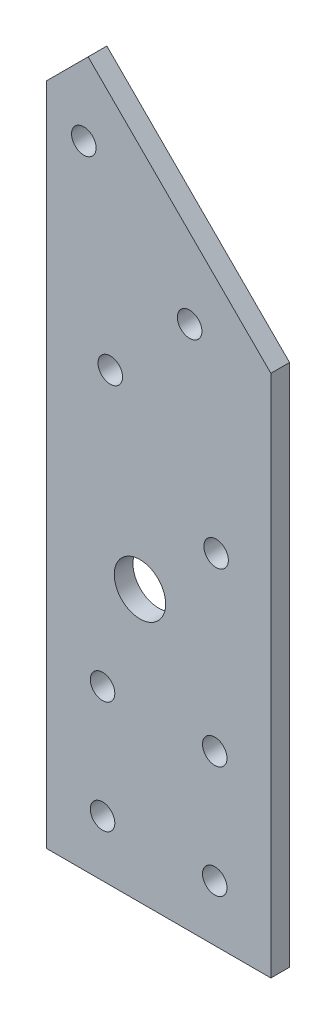
SolidWorks part; units mm, degrees
material "6061-T6 (SS)"
ref_plane "Front" through (0, 0, 0) normal (0, 0, 1) x (1, 0, 0)
ref_plane "Top" through (0, 0, 0) normal (0, 1, 0) x (1, 0, 0)
ref_plane "Right" through (0, 0, 0) normal (1, 0, 0) x (0, 0, -1)
sketch "Sketch1" plane through (0, 0, 0) normal (0, 0, 1) x (1, 0, 0)
  line L0 (0, 0) -> (76.2, 0)
  line L1 (76.2, 0) -> (76.2, 177.8)
  line L2 (76.2, 177.8) -> (14.1602, 239.8398)
  line L3 (0, 225.6796) -> (0, 0)
  line L4 (14.1602, 239.8398) -> (0, 225.6796)
  dimension "D1" = 76.2
  dimension "D2" = 177.8
  dimension "D3" = 45
  dimension "D4" = 20.0255
extrude "Boss-Extrude1" add sketch "Sketch1" along normal blind 6.35
hole_wizard "21/64 (0.32813) Diameter Hole1" positions "Sketch2" profile "Sketch3" hole size "21/64" standard "ANSI Inch" end condition through all
sketch "Sketch2" plane through (0, 0, 6.35) normal (0, 0, 1) x (1, 0, 0)
  line L0 (76.2, 0) -> (76.2, 177.8) construction
  line L1 (0, 0) -> (76.2, 0) construction
  point P0 (57.15, 19.05)
  dimension "D1" = 19.05
  dimension "D2" = 19.05
sketch "Sketch3" plane through (57.15, 19.05, 6.35) normal (1, 0, 0) x (0, -1, 0)
  line L0 (0, 0) -> (0, 6.35)
  line L1 (0, 6.35) -> (4.1673, 6.35)
  line L2 (4.1673, 6.35) -> (4.1673, 0)
  line L5 (4.1673, 0) -> (0, 0)
  line L11 (0, -6.35) -> (0, 107.95) construction
  dimension "Thru Hole Dia." = 8.3345
  dimension "Thru Hole Depth" = 6.35
pattern_linear "LPattern1" count 2 spacing 38.1 along (-1, 0, 0) count 2 spacing 38.1 along (0, 1, 0) of "21/64 (0.32813) Diameter Hole1"
hole_wizard "21/64 (0.32813) Diameter Hole2" positions "Sketch4" profile "Sketch5" hole size "21/64" standard "ANSI Inch" end condition through all
sketch "Sketch4" plane through (0, 0, 6.35) normal (0, 0, 1) x (1, 0, 0)
  line L0 (76.2, 177.8) -> (14.1602, 239.8398) construction
  line L1 (0, 225.6796) -> (0, 0) construction
  point P0 (12.7, 214.3592)
  dimension "D1" = 19.05
  dimension "D2" = 12.7
sketch "Sketch5" plane through (12.7, 214.3592, 6.35) normal (1, 0, 0) x (0, -1, 0)
  line L0 (0, 0) -> (0, 6.35)
  line L1 (0, 6.35) -> (4.1673, 6.35)
  line L2 (4.1673, 6.35) -> (4.1673, 0)
  line L5 (4.1673, 0) -> (0, 0)
  line L11 (0, -6.35) -> (0, 107.95) construction
  dimension "Thru Hole Dia." = 8.3345
  dimension "Thru Hole Depth" = 6.35
pattern_linear "LPattern2" count 3 spacing 50.8 along (0.7071, -0.7071, 0) count 2 spacing 38.1 along (-0.7071, -0.7071, 0) skipping (0, 1), (2, 0) of "21/64 (0.32813) Diameter Hole2"
hole_wizard "11/16 (0.6875) Diameter Hole1" positions "Sketch6" profile "Sketch7" hole size "11/16" standard "ANSI Inch" end condition through all
sketch "Sketch6" plane through (0, 0, 6.35) normal (0, 0, 1) x (1, 0, 0)
  line L0 (0, 225.6796) -> (0, 0) construction
  line L1 (0, 0) -> (76.2, 0) construction
  point P0 (31.75, 92.075)
  dimension "D1" = 31.75
  dimension "D2" = 92.075
sketch "Sketch7" plane through (31.75, 92.075, 6.35) normal (1, 0, 0) x (0, -1, 0)
  line L0 (0, 0) -> (0, 6.35)
  line L1 (0, 6.35) -> (8.7312, 6.35)
  line L2 (8.7312, 6.35) -> (8.7312, 0)
  line L5 (8.7312, 0) -> (0, 0)
  line L11 (0, -6.35) -> (0, 107.95) construction
  dimension "Thru Hole Dia." = 17.4625
  dimension "Thru Hole Depth" = 6.35
